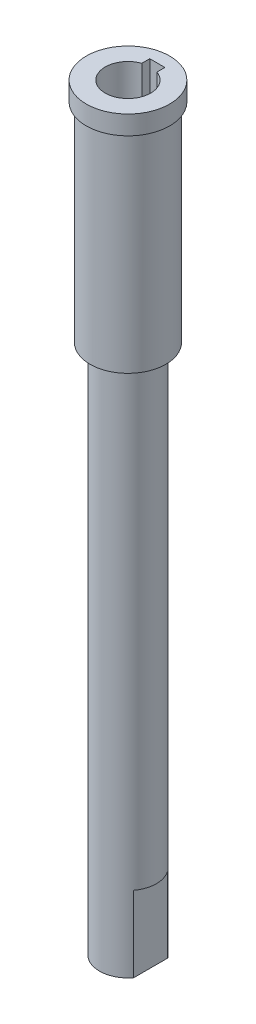
SolidWorks part; units mm, degrees
other "Markup1"
sketch "Sketch8" plane through (-11, 200, -11) normal (-0.0758, 0.9971, -0.0055) x (0.997, 0.0759, 0.0134)
material "AISI 304"
ref_plane "前视基准面" through (0, 0, 0) normal (0, 0, 1) x (1, 0, 0)
ref_plane "上视基准面" through (0, 0, 0) normal (0, 1, 0) x (1, 0, 0)
ref_plane "右视基准面" through (0, 0, 0) normal (1, 0, 0) x (0, 0, -1)
sketch "Sketch2" plane through (0, 0, 0) normal (0, 1, 0) x (1, 0, 0)
  circle A0 centre (0, 0) radius 10
  dimension "D1" = 20
extrude "Extrude1" add sketch "Sketch2" along normal blind 200
sketch "Sketch3" plane through (0, 200, 0) normal (0, 1, 0) x (1, 0, 0)
  line L2 (2, 5.6569) -> (2, 7.7493)
  line L3 (2, 7.7493) -> (-2, 7.7493)
  line L4 (-2, 5.6569) -> (-2, 7.7493)
  line L5 (2.9935, 3.3817) -> (-2, 7.7493) construction
  line L6 (2, 7.7493) -> (-2.9935, 3.3817) construction
  arc A0 (-2, 5.6569) -> (2, 5.6569) centre (0, 0) ccw
  point P3 (0, 6)
  dimension "D1" = 12
  dimension "D2" = 4
extrude "Extrude2" cut sketch "Sketch3" against normal blind 30
sketch "Sketch5" plane through (0, 0, 0) normal (0, -1, 0) x (1, 0, 0)
  circle A0 centre (0, 0) radius 7.5
  circle A2 centre (0, 0) radius 10 construction
  dimension "D1" = 2.5
extrude "Extrude4" cut sketch "Sketch5" against normal blind 140 flip side to cut
sketch "Sketch6" plane through (0, 200, 0) normal (0, 1, 0) x (1, 0, 0)
  circle A0 centre (0, 0) radius 8.6307
  circle A1 centre (0, 0) radius 11
  circle A2 centre (0, 0) radius 10 construction
  dimension "D1" = 1
extrude "Extrude5" add sketch "Sketch6" against normal blind 5
sketch "Sketch7" plane through (0, 0, 0) normal (0, -1, 0) x (1, 0, 0)
  line L1 (17.8671, 23.4714) -> (6, 23.4714)
  line L2 (17.8671, 23.4714) -> (17.8671, -10.1519)
  line L3 (17.8671, -10.1519) -> (6, -10.1519)
  line L4 (6, 23.4714) -> (6, -10.1519)
  line L5 (17.8671, 23.4714) -> (6, -10.1519) construction
  line L6 (17.8671, -10.1519) -> (6, 23.4714) construction
  point P0 (11.9335, 6.6598)
  dimension "D1" = 6
extrude "Extrude6" cut sketch "Sketch7" against normal blind 20
